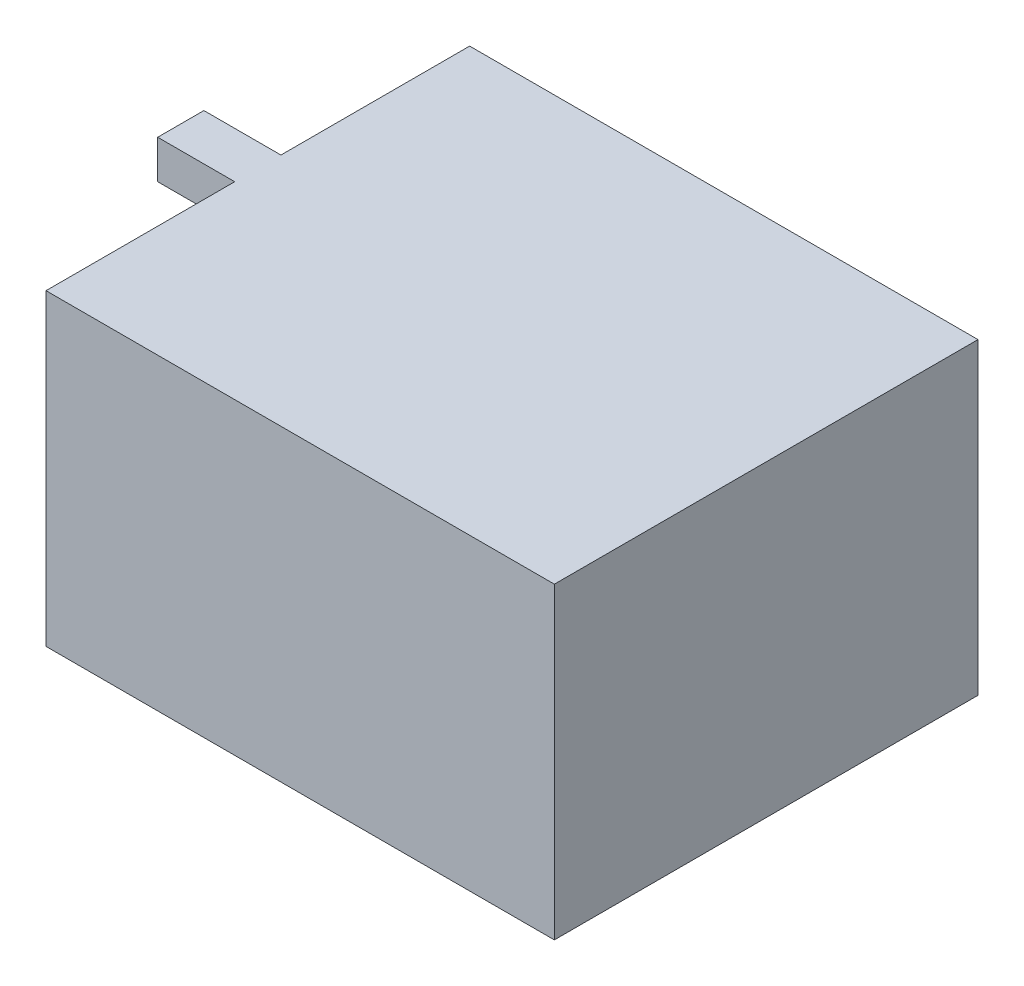
SolidWorks part; units mm, degrees
ref_plane "前视基准面" through (0, 0, 0) normal (0, 0, 1) x (1, 0, 0)
ref_plane "上视基准面" through (0, 0, 0) normal (0, 1, 0) x (1, 0, 0)
ref_plane "右视基准面" through (0, 0, 0) normal (1, 0, 0) x (0, 0, -1)
sketch "草图1" plane through (0, 0, 0) normal (0, 1, 0) x (1, 0, 0)
  line L1 (-33, 27.5) -> (33, 27.5)
  line L2 (-33, 27.5) -> (-33, -27.5)
  line L3 (-33, -27.5) -> (33, -27.5)
  line L4 (33, 27.5) -> (33, -27.5)
  line L5 (-33, 27.5) -> (33, -27.5) construction
  line L6 (-33, -27.5) -> (33, 27.5) construction
  point P0 (0, 0)
  dimension "D1" = 66
  dimension "D2" = 55
extrude "凸台-拉伸1" add sketch "草图1" along normal blind 40
sketch "草图2" plane through (-33, 0, 0) normal (-1, 0, 0) x (0, 0, 1)
  line L1 (-27.5, 40) -> (27.5, 40) construction
  line L3 (-3, 35) -> (3, 35)
  line L4 (-3, 35) -> (-3, 40)
  line L5 (-3, 40) -> (3, 40)
  line L6 (3, 35) -> (3, 40)
  line L7 (-3, 35) -> (3, 40) construction
  line L8 (-3, 40) -> (3, 35) construction
  point P0 (0, 40)
  point P5 (0, 37.5)
  dimension "D1" = 5
  dimension "D2" = 6
extrude "凸台-拉伸2" add sketch "草图2" along normal blind 10
